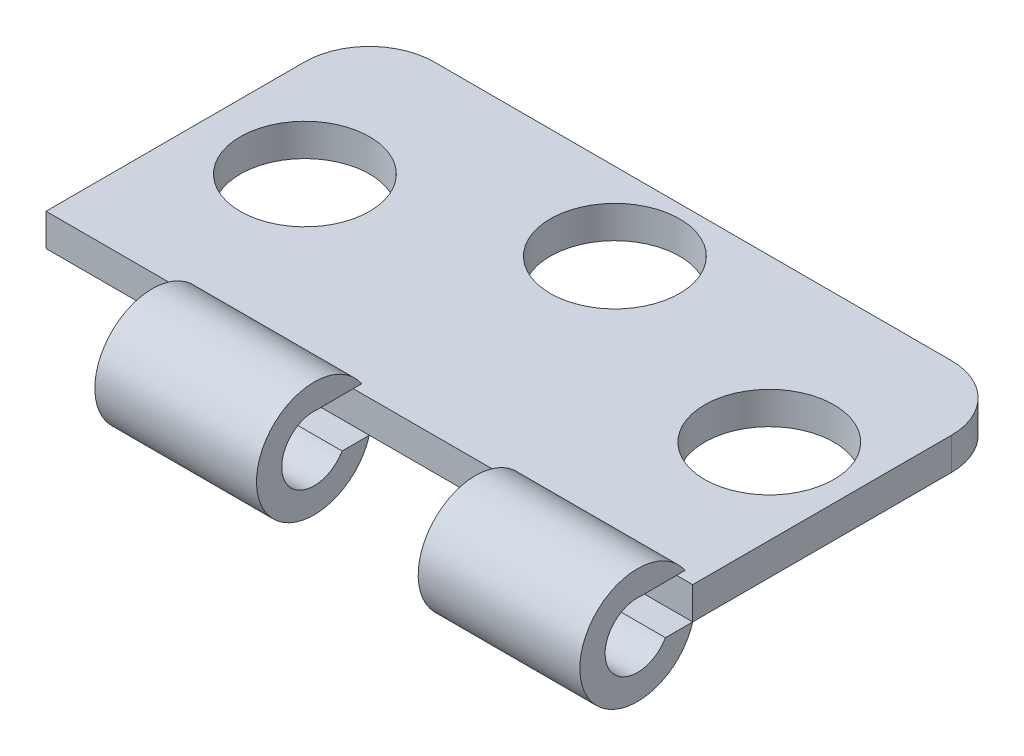
SolidWorks part; units mm, degrees
ref_plane "Front Plane" through (0, 0, 0) normal (0, 0, 1) x (1, 0, 0)
ref_plane "Top Plane" through (0, 0, 0) normal (0, 1, 0) x (1, 0, 0)
ref_plane "Right Plane" through (0, 0, 0) normal (1, 0, 0) x (0, 0, -1)
sketch "Sketch2" plane through (0, 0, 0) normal (0, 1, 0) x (1, 0, 0)
  line L1 (-100, -50) -> (100, -50)
  line L2 (-100, -50) -> (-100, 30)
  line L3 (-80, 50) -> (80, 50)
  line L4 (100, -50) -> (100, 30)
  line L5 (-100, -50) -> (100, 50) construction
  line L6 (-100, 50) -> (100, -50) construction
  circle A0 centre (0, 25.9398) radius 20
  circle A1 centre (73.6842, 0) radius 20
  circle A2 centre (-69.9248, 0) radius 20
  arc A3 (100, 30) -> (80, 50) centre (80, 30) ccw
  arc A4 (-80, 50) -> (-100, 30) centre (-80, 30) ccw
  point P0 (0, 0)
  dimension "D6" = 20
  dimension "D1" = 200
  dimension "D2" = 100
extrude "Boss-Extrude2" add sketch "Sketch2" along normal blind 10
sketch "Sketch3" plane through (100, 0, 0) normal (1, 0, 0) x (0, 0, -1)
  line L0 (-50, 0) -> (-58.4331, 0)
  line L1 (-58.4331, 10) -> (-50, 10)
  line L2 (-52.3497, 14.9903) -> (-65.9482, 14.9342)
  arc A2 (-65.9482, 14.9342) -> (-58.4331, 10) centre (-67.0933, 5) ccw
  arc A3 (-52.3497, 14.9903) -> (-50, 0) centre (-67.0933, 5) ccw
extrude "Boss-Extrude5" add sketch "Sketch3" against normal blind 50 separate body contours L2 A3 L0 A2
pattern_linear "LPattern1" count 2 spacing 100 along (-1, 0, 0) of "Boss-Extrude5"
